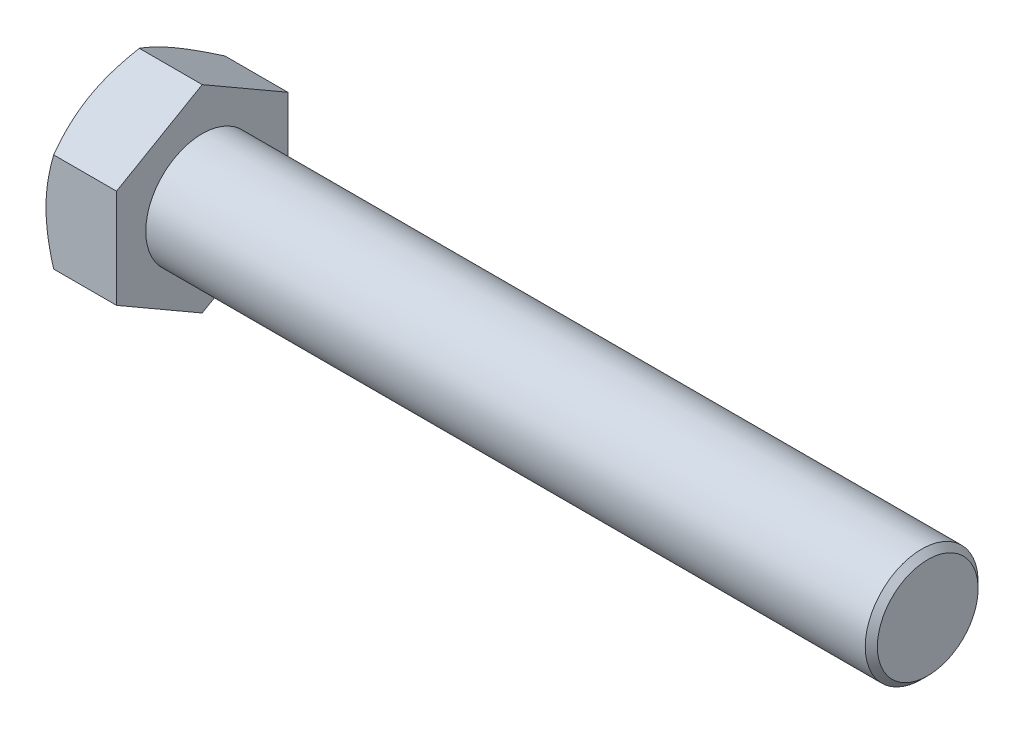
SolidWorks part; units mm, degrees
ref_plane "Front Plane" through (0, 0, 0) normal (0, 0, 1) x (1, 0, 0)
ref_plane "Top Plane" through (0, 0, 0) normal (0, 1, 0) x (1, 0, 0)
ref_plane "Right Plane" through (0, 0, 0) normal (1, 0, 0) x (0, 0, -1)
other "Configuration Table"
sketch "BaseHeadSke" plane through (0, 0, 0) normal (1, 0, 0) x (0, 0, -1)
  line L1 (0, 49.0748) -> (-42.5, 24.5374)
  line L2 (-42.5, 24.5374) -> (-42.5, -24.5374)
  line L3 (-42.5, -24.5374) -> (0, -49.0748)
  line L4 (0, -49.0748) -> (42.5, -24.5374)
  line L5 (42.5, -24.5374) -> (42.5, 24.5374)
  line L6 (42.5, 24.5374) -> (0, 49.0748)
  circle A0 centre (0, 0) radius 42.5 construction
extrude "BaseHead" add sketch "BaseHeadSke" along normal blind 35
sketch "HeadChamferSke" plane through (0, 0, 0) normal (0, 0, 1) x (1, 0, 0)
  line L0 (0, 0) -> (108.1848, 0) construction
  line L1 (0, 24.5374) -> (0, -24.5374) construction
  line L2 (0, 49.0748) -> (0, 42.5)
  line L3 (0, 42.5) -> (3.7959, 49.0748)
  line L4 (3.7959, 49.0748) -> (0, 49.0748)
  line L7 (35, 49.0748) -> (0, 49.0748) construction
  dimension "Angle_Chamfer_Head" = 30
revolve "HeadChamfer" cut sketch "HeadChamferSke" angle 360 about L0
sketch "BodySke" plane through (0, 0, 0) normal (0, 0, 1) x (1, 0, 0)
  line L0 (0, 0) -> (440.8544, 0) construction
  line L1 (0, 0) -> (0, 28)
  line L3 (0, 36.8061) -> (0, 0) construction
  line L4 (0, 28) -> (391.9855, 28)
  line L5 (391.9855, 28) -> (395, 24.9855)
  line L6 (395, 24.9855) -> (395, 0)
  line L7 (395, 0) -> (0, 0)
  line L8 (40.5, 0) -> (40.5, 20.794) construction
  line L9 (35, 24.5374) -> (35, -24.5374) construction
  line L10 (35, 0) -> (35, 20.794) construction
  dimension "Thread_minor" = 13.797
  dimension "Body_Chamfer_Angle" = 45
  dimension "Advance" = 2
revolve "BaseBody" add sketch "BodySke" angle 360 about L0
cosmetic thread "ThreadCosmetic" [suppressed] parameters "Thread_minor"=13.797
sketch "BearingFaceSke" plane through (0, 0, 0) normal (0, 0, 1) x (1, 0, 0)
  line L0 (0, 0) -> (414.2241, 0) construction
  line L1 (35, 49.0748) -> (35, 24.5374) construction
  line L2 (35, 42.5) -> (34, 42.5)
  line L3 (35, 42.5) -> (35, 52.5)
  line L4 (35, 52.5) -> (34, 52.5)
  line L5 (34, 42.5) -> (34, 52.5)
  dimension "D1" = 10
  dimension "D2" = 24
revolve "BearingFace" [suppressed] cut sketch "BearingFaceSke" angle 360 about L0
fillet "HeadFillet" [suppressed] radius 2
sketch "ThdSchSke" plane through (0, 0, 0) normal (0, 0, 1) x (1, 0, 0)
  line L0 (0, 0) -> (453.2163, 0) construction
  line L1 (386.4855, 31.4808) -> (386.4855, 28)
  line L2 (386.4855, 31.4808) -> (389.9663, 31.4808)
  line L3 (389.9663, 31.4808) -> (389.9663, 28)
  line L4 (389.9663, 28) -> (388.2259, 24.9855)
  line L5 (388.2259, 24.9855) -> (386.4855, 28)
  dimension "D1" = 2
revolve "ThreadSchematic" [suppressed] cut sketch "ThdSchSke" angle 360 about L0
pattern_linear "ThdSchPat" [suppressed]
equation "\"Thread_minor@ThreadCosmetic\" = \"Thread_minor@BodySke\""
equation "\"D2@BearingFaceSke\" = \"Width_flats@BaseHeadSke\""
equation "\"D1@ThdSchSke\" = \"Advance@BodySke\""
equation "\"Advance@ThdSchPat\" = \"Advance@BodySke\""
equation "\"Tooth_Num@ThdSchPat\" =  int( \"Thread_length@BodySke\" / \"Advance@BodySke\" ) - 1 "
